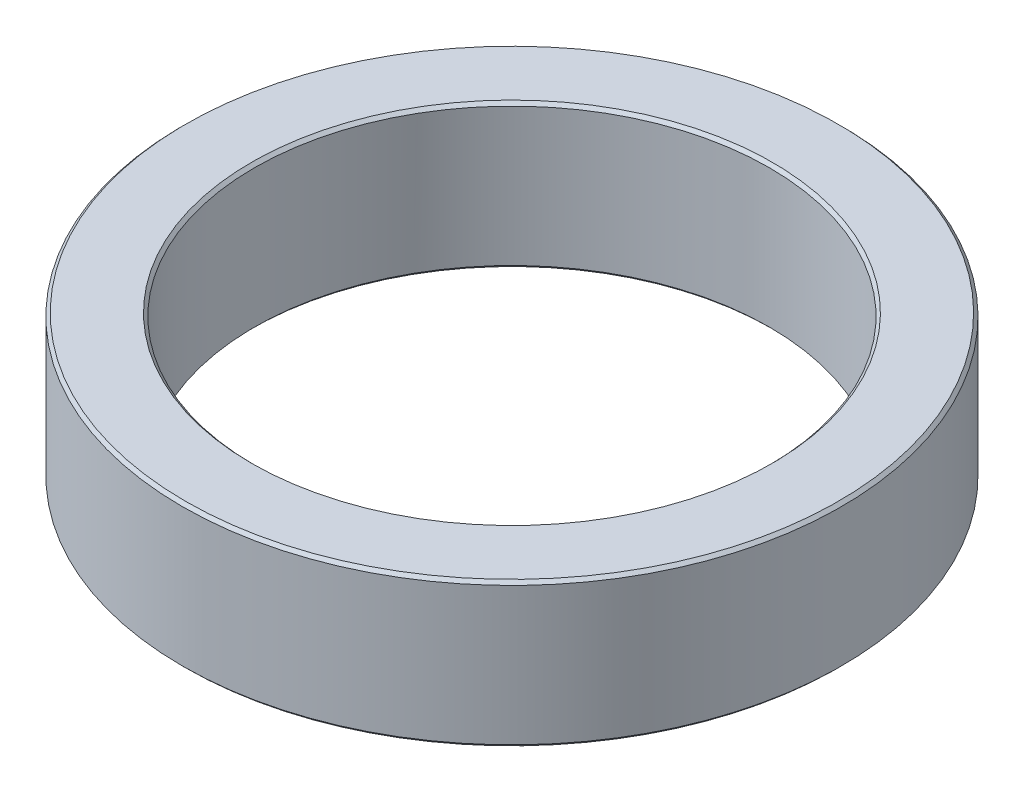
SolidWorks part; units mm, degrees
ref_plane "Front Plane" through (0, 0, 0) normal (0, 0, 1) x (1, 0, 0)
ref_plane "Top Plane" through (0, 0, 0) normal (0, 1, 0) x (1, 0, 0)
ref_plane "Right Plane" through (0, 0, 0) normal (1, 0, 0) x (0, 0, -1)
sketch "Sketch1" plane through (0, 0, 0) normal (0, 1, 0) x (1, 0, 0)
  circle A0 centre (0, 0) radius 12.5
  circle A1 centre (0, 0) radius 16
  dimension "D1" = 32
  dimension "D2" = 25
extrude "Boss-Extrude1" add sketch "Sketch1" along normal blind 7
chamfer "Chamfer1" distance 0.15 angle 45 4 edges at (0, 7, 12.5) (0, 0, 12.5) (0, 0, 16) (0, 7, 16)
